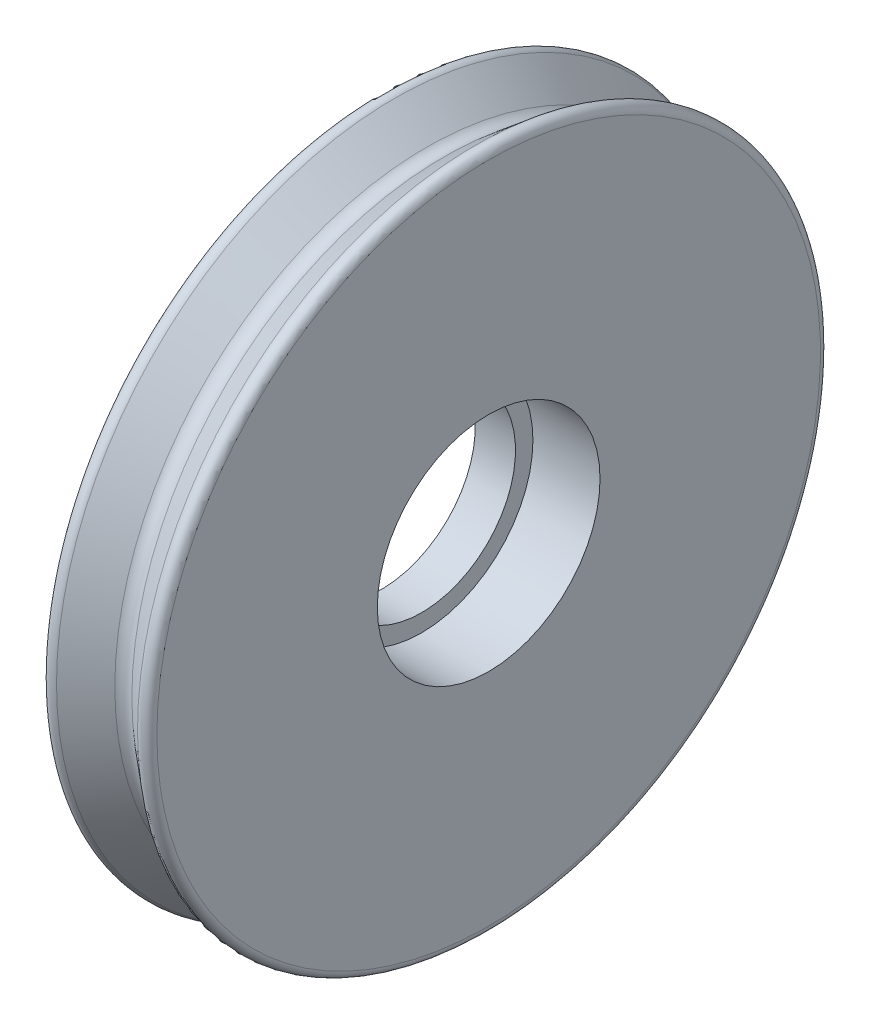
SolidWorks part; units mm, degrees
material "ABS"
ref_plane "Front Plane" through (0, 0, 0) normal (0, 0, 1) x (1, 0, 0)
ref_plane "Top Plane" through (0, 0, 0) normal (0, 1, 0) x (1, 0, 0)
ref_plane "Right Plane" through (0, 0, 0) normal (1, 0, 0) x (0, 0, -1)
sketch "Sketch1" plane through (0, 0, 0) normal (0, 0, 1) x (1, 0, 0)
  line L0 (0, 3.5) -> (0, 13)
  line L2 (0, 13) -> (1.6821, 11.6141)
  line L3 (2.3179, 11.6141) -> (4, 13)
  line L5 (4, 13) -> (4, 4.15)
  line L6 (4, 4.15) -> (1.5, 4.15)
  line L7 (1.5, 4.15) -> (1.5, 3.5)
  line L8 (1.5, 3.5) -> (0, 3.5)
  line L9 (0, 0) -> (4, 0) construction
  arc A0 (1.6821, 11.6141) -> (2.3179, 11.6141) centre (2, 12) ccw
  dimension "D8" = 0.5
  dimension "D1" = 12
  dimension "D2" = 4
  dimension "D3" = 2.5
  dimension "D4" = 4.15
  dimension "D5" = 3.5
  dimension "D6" = 13
  dimension "D9" = 2
revolve "Revolve1" add sketch "Sketch1" angle 360 about L9
ref_plane "Plane1" through (2, 0, 0) normal (-1, 0, 0) x (0, 0, 1)
fillet "Fillet1" radius 0.3 2 edges at (4, 0, 13) (0, 0, 13)
